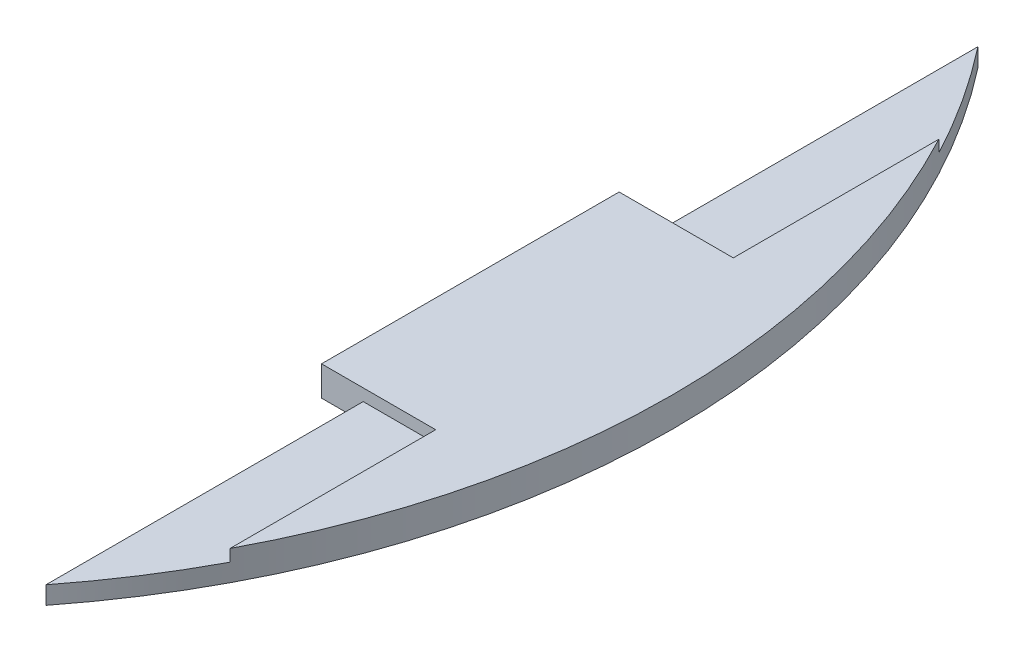
SolidWorks part; units mm, degrees
ref_plane "Front Plane" through (0, 0, 0) normal (0, 0, 1) x (1, 0, 0)
ref_plane "Top Plane" through (0, 0, 0) normal (0, 1, 0) x (1, 0, 0)
ref_plane "Right Plane" through (0, 0, 0) normal (1, 0, 0) x (0, 0, -1)
sketch "Sketch1" plane through (0, 0, 0) normal (0, 1, 0) x (1, 0, 0)
  line L0 (50, -12.5) -> (50, -39.144)
  line L1 (-46.5, 12.5) -> (46.5, 12.5) construction
  line L2 (-46.5, 12.5) -> (-46.5, -12.5) construction
  line L3 (-46.5, -12.5) -> (46.5, -12.5) construction
  line L4 (46.5, 12.5) -> (46.5, -12.5) construction
  line L5 (-46.5, 12.5) -> (46.5, -12.5) construction
  line L6 (-46.5, -12.5) -> (46.5, 12.5) construction
  line L7 (46.5, 12.5) -> (50, 12.5)
  line L8 (46.5, 12.5) -> (46.5, -12.5)
  line L9 (46.5, -12.5) -> (50, -12.5)
  line L12 (50, 39.144) -> (50, 12.5)
  circle A0 centre (0, 0) radius 63.5 construction
  arc A1 (50, 39.144) -> (50, -39.144) centre (0, 0) cw
  dimension "D1" = 127
  dimension "D2" = 25
  dimension "D3" = 46.5
  dimension "D4" = 50
extrude "Boss-Extrude1" add sketch "Sketch1" along normal blind 2.5
sketch "Sketch2" plane through (0, 2.5, 0) normal (0, 1, 0) x (1, 0, 0)
  line L0 (46.5, 0) -> (67.028, 0) construction
  line L1 (50, 12.5) -> (56.089, 12.5)
  line L2 (50, 12.5) -> (50, 42.3172)
  line L3 (50, 42.3172) -> (56.089, 42.3172)
  line L4 (56.089, 12.5) -> (56.089, 42.3172)
  line L5 (46.5, 12.5) -> (46.5, -12.5) construction
  line L6 (50, -42.3172) -> (56.089, -42.3172)
  line L7 (56.089, -12.5) -> (56.089, -42.3172)
  line L8 (50, -12.5) -> (56.089, -12.5)
  line L9 (50, -12.5) -> (50, -42.3172)
  dimension "D1" = 56.089
extrude "Cut-Extrude1" cut sketch "Sketch2" against normal blind 1
